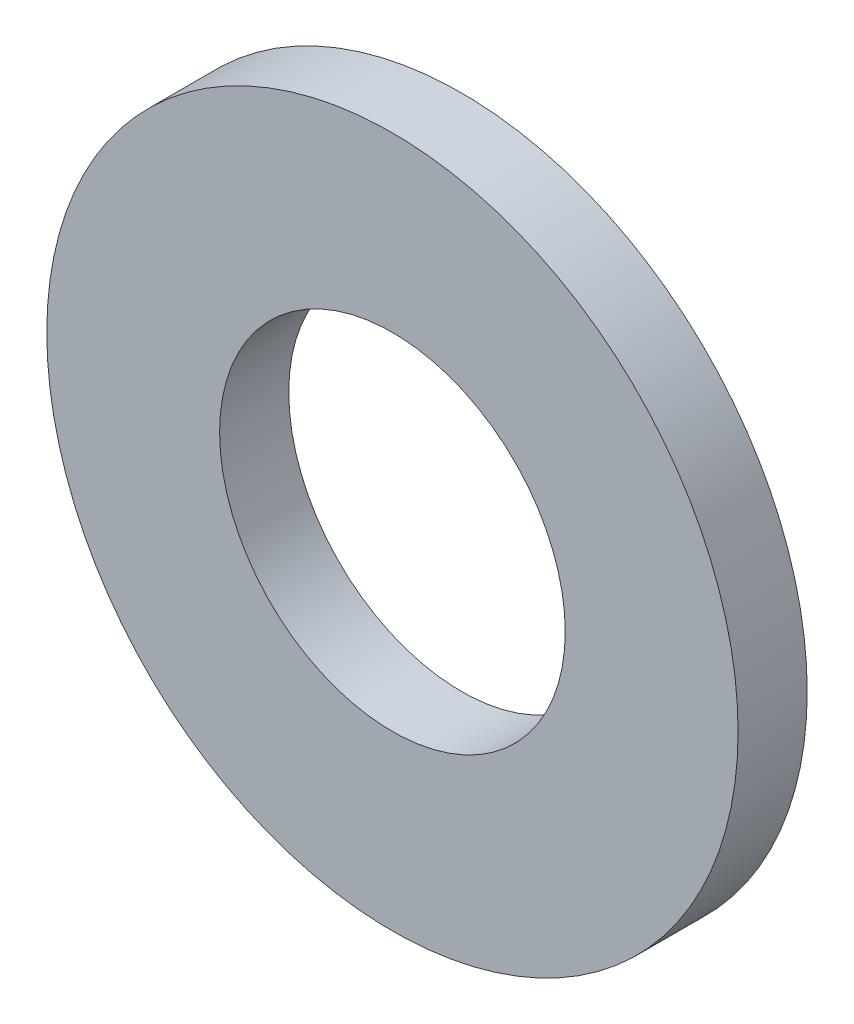
SolidWorks part; units mm, degrees
ref_plane "Front Plane" through (0, 0, 0) normal (0, 0, 1) x (1, 0, 0)
ref_plane "Top Plane" through (0, 0, 0) normal (0, 1, 0) x (1, 0, 0)
ref_plane "Right Plane" through (0, 0, 0) normal (1, 0, 0) x (0, 0, -1)
sketch "Sketch1" plane through (0, 0, 0) normal (0, 0, 1) x (1, 0, 0)
  circle A0 centre (0, 0) radius 12.5
  circle A1 centre (0, 0) radius 25
  dimension "D1" = 25
  dimension "D2" = 50
extrude "Boss-Extrude1" add sketch "Sketch1" along normal blind 5
